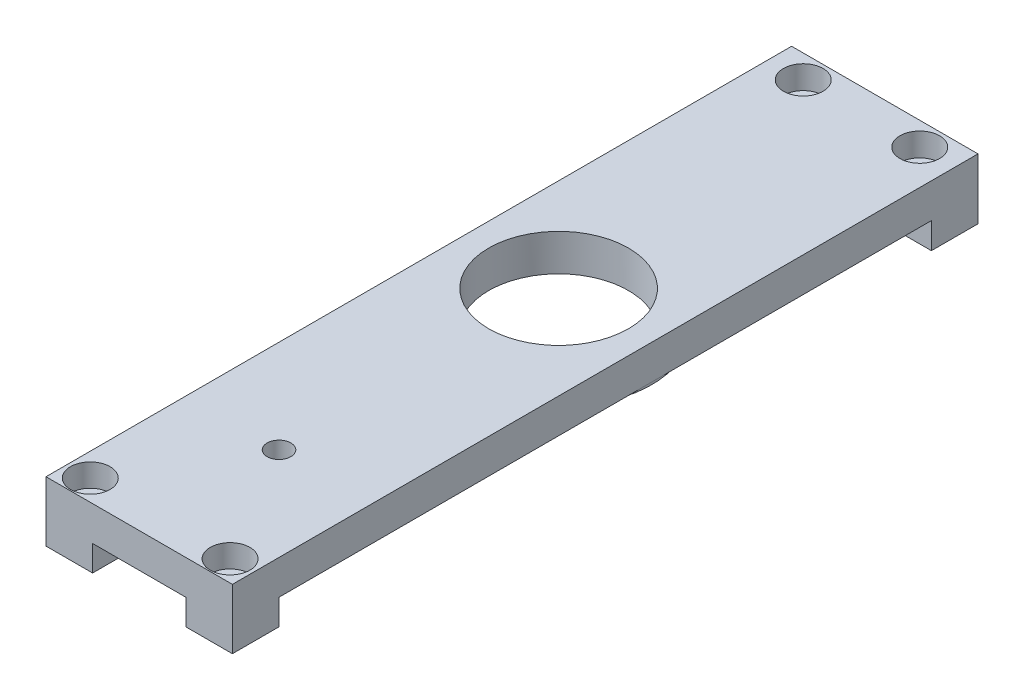
SolidWorks part; units mm, degrees
ref_plane "Ebene vorne" through (0, 0, 0) normal (0, 0, 1) x (1, 0, 0)
ref_plane "Ebene oben" through (0, 0, 0) normal (0, 1, 0) x (1, 0, 0)
ref_plane "Ebene rechts" through (0, 0, 0) normal (1, 0, 0) x (0, 0, -1)
sketch "Skizze1" plane through (0, 0, 0) normal (0, 0, 1) x (1, 0, 0)
  line L1 (0, 0) -> (40, 0)
  line L2 (0, 0) -> (0, 13)
  line L3 (0, 13) -> (40, 13)
  line L4 (40, 0) -> (40, 13)
  dimension "D1" = 40
  dimension "D2" = 13
extrude "Aufsatz-Linear austragen1" add sketch "Skizze1" along normal blind 10
sketch "Skizze3" plane through (0, 0, 10) normal (0, 0, 1) x (1, 0, 0)
  line L0 (40, 0) -> (40, 13) construction
  line L1 (0, 13) -> (40, 13)
  line L2 (0, 13) -> (0, 5.6)
  line L3 (0, 5.6) -> (40, 5.6)
  line L4 (40, 13) -> (40, 5.6)
  dimension "D1" = 7.4
extrude "Aufsatz-Linear austragen3" add sketch "Skizze3" along normal blind 150
sketch "Skizze4" plane through (0, 5.6, 0) normal (0, -1, 0) x (1, 0, 0)
  line L0 (0, 10) -> (40, 10) construction
  line L2 (40, 160) -> (40, 10) construction
  circle A0 centre (20, 70) radius 15
  dimension "D3" = 30
  dimension "D1" = 60
  dimension "D2" = 20
extrude "Schnitt-Linear austragen1" cut sketch "Skizze4" against normal blind 11 and the other way through all
sketch "Skizze7" plane through (0, 5.6, 0) normal (0, -1, 0) x (1, 0, 0)
  circle A0 centre (20, 70) radius 20
extrude "Aufsatz-Linear austragen4" add sketch "Skizze7" along normal blind 0.5
sketch "Skizze5" plane through (0, 5.6, 0) normal (0, -1, 0) x (-1, 0, 0)
  line L0 (0, -160) -> (0, -70) construction
  circle A0 centre (-20, -130) radius 2.55
  circle A1 centre (-20, -70) radius 15 construction
  dimension "D3" = 5.1
  dimension "D1" = 20
  dimension "D2" = 60
extrude "Schnitt-Linear austragen2" cut sketch "Skizze5" against normal blind 150
sketch "Skizze8" plane through (0, 5.6, 0) normal (0, 1, 0) x (1, 0, 0)
  circle A0 centre (20, -70) radius 15
extrude "Schnitt-Linear austragen4" cut sketch "Skizze8" against normal blind 0.5
sketch "Skizze10" plane through (0, 0, 0) normal (0, -1, 0) x (1, 0, 0)
  line L0 (0, 0) -> (40, 0) construction
  line L1 (40, 10) -> (40, 0) construction
  line L2 (0, 10) -> (0, 0) construction
  circle A0 centre (7.5, 5) radius 2.5
  circle A1 centre (32.5, 5) radius 2.5
  dimension "D5" = 5
  dimension "D6" = 5
  dimension "D1" = 5
  dimension "D2" = 5
  dimension "D3" = 7.5
  dimension "D4" = 7.5
extrude "Schnitt-Linear austragen5" cut sketch "Skizze10" against normal blind 17
sketch "Skizze15" plane through (0, 13, 0) normal (0, 1, 0) x (1, 0, 0)
  circle A0 centre (7.5, -5) radius 4.25
  circle A1 centre (32.5, -5) radius 4.25
  dimension "D1" = 8.5
  dimension "D2" = 8.5
extrude "Schnitt-Linear austragen7" cut sketch "Skizze15" against normal blind 5
sketch "Skizze16" plane through (0, 5.6, 0) normal (0, -1, 0) x (1, 0, 0)
  line L1 (0, 160) -> (10, 160)
  line L2 (0, 160) -> (0, 150)
  line L3 (0, 150) -> (10, 150)
  line L4 (10, 160) -> (10, 150)
  line L5 (40, 160) -> (30, 160)
  line L6 (40, 160) -> (40, 150)
  line L7 (40, 150) -> (30, 150)
  line L8 (30, 160) -> (30, 150)
  dimension "D1" = 10
  dimension "D2" = 10
  dimension "D3" = 10
  dimension "D4" = 10
extrude "Aufsatz-Linear austragen5" add sketch "Skizze16" along normal blind 5.5
sketch "Skizze17" plane through (0, 13, 0) normal (0, 1, 0) x (1, 0, 0)
  line L0 (0, -160) -> (0, 0) construction
  line L1 (40, -160) -> (40, 0) construction
  line L4 (40, -160) -> (0, -160) construction
  circle A0 centre (5, -155.5) radius 2.5
  circle A1 centre (35, -155.5) radius 2.5
  dimension "D3" = 5
  dimension "D4" = 5
  dimension "D1" = 5
  dimension "D2" = 5
  dimension "D5" = 4.5
  dimension "D6" = 4.5
extrude "Schnitt-Linear austragen8" cut sketch "Skizze17" against normal blind 21.6
sketch "Skizze18" plane through (0, 13, 0) normal (0, 1, 0) x (1, 0, 0)
  circle A0 centre (5, -155.5) radius 4.25
  circle A1 centre (35, -155.5) radius 4.25
  dimension "D1" = 8.5
  dimension "D2" = 8.5
extrude "Schnitt-Linear austragen9" cut sketch "Skizze18" against normal blind 4.9
